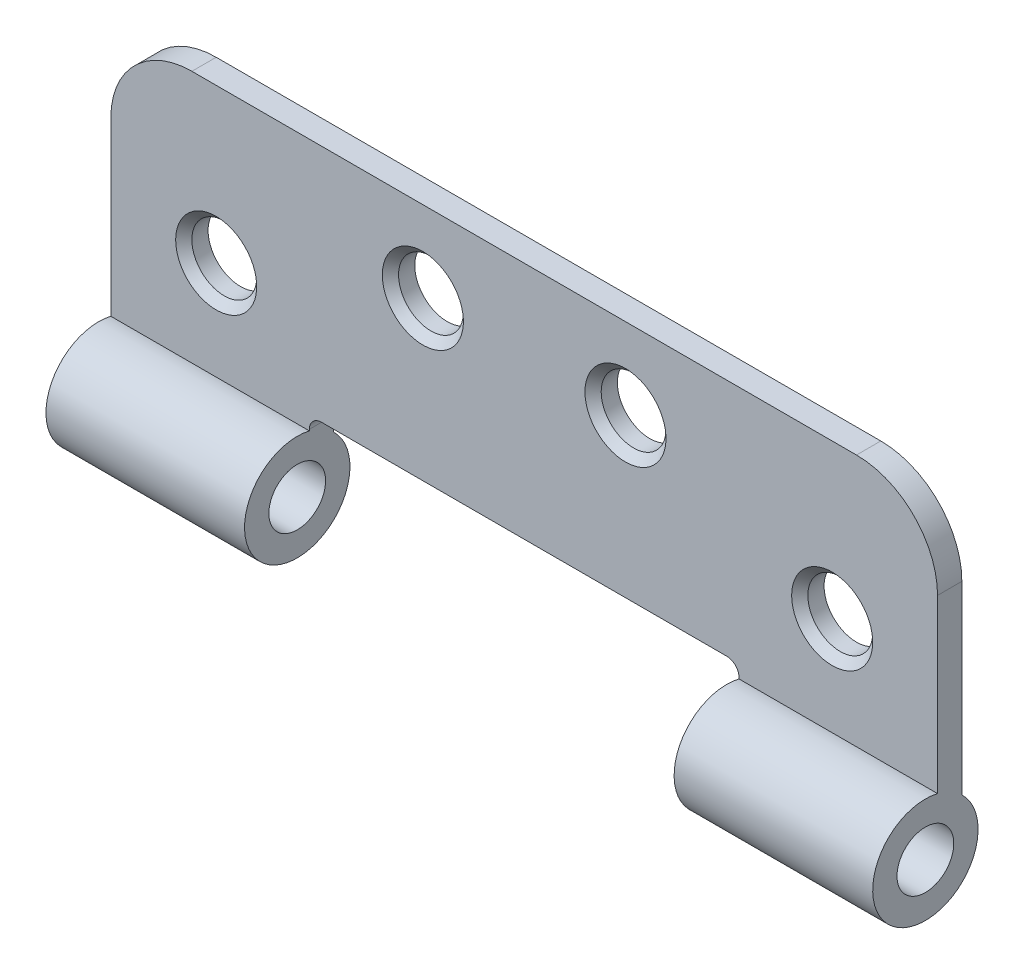
SolidWorks part; units mm, degrees
ref_plane "Front Plane" through (0, 0, 0) normal (0, 0, 1) x (1, 0, 0)
ref_plane "Top Plane" through (0, 0, 0) normal (0, 1, 0) x (1, 0, 0)
ref_plane "Right Plane" through (0, 0, 0) normal (1, 0, 0) x (0, 0, -1)
sketch "Sketch1" plane through (0, 0, 0) normal (0, 0, 1) x (1, 0, 0)
  line L1 (-51, 0) -> (51, 0)
  line L2 (-51, 0) -> (-51, 27.5)
  line L3 (-41, 37.5) -> (41, 37.5)
  line L4 (51, 0) -> (51, 27.5)
  arc A0 (41, 37.5) -> (51, 27.5) centre (41, 27.5) cw
  arc A1 (-51, 27.5) -> (-41, 37.5) centre (-41, 27.5) cw
  circle A2 centre (-38, 18.5) radius 4
  circle A3 centre (38, 18.5) radius 4
  circle A4 centre (-12.5, 27.5) radius 4
  circle A5 centre (12.5, 27.5) radius 4
  point P4 (0, 0)
  point P8 (51, 37.5)
  point P11 (-51, 37.5)
  point P21 (0, 37.5)
  dimension "D3" = 10
  dimension "D4" = 8
  dimension "D5" = 18.5
  dimension "D6" = 27.5
  dimension "D7" = 25
  dimension "D9" = 76
  dimension "D1" = 102
  dimension "D2" = 37.5
  dimension "D8" = 12.5
  dimension "D10" = 38
extrude "Boss-Extrude1" add sketch "Sketch1" along normal blind 3
sketch "Sketch2" plane through (-51, 0, 0) normal (-1, 0, 0) x (0, 0, 1)
  line L0 (0, 27.5) -> (0, 0) construction
  circle A0 centre (4.5, 0) radius 6.5
  dimension "D1" = 13
  dimension "D2" = 4.5
extrude "Boss-Extrude2" add sketch "Sketch2" against normal up to surface (102 mm away) up to face at (51, 13.75, 1.5)
sketch "Sketch3" plane through (-51, 0, 0) normal (-1, 0, 0) x (0, 0, 1)
  circle A0 centre (4.5, 0) radius 3.5
  dimension "D1" = 7
extrude "Cut-Extrude1" cut sketch "Sketch3" against normal through all
sketch "Sketch4" plane through (0, 0, 3) normal (0, 0, 1) x (1, 0, 0)
  line L0 (41, 37.5) -> (-41, 37.5) construction
  line L1 (-26.5, 8) -> (26.5, 8)
  line L2 (-26.5, 8) -> (-26.5, -6.5)
  line L3 (-26.5, -6.5) -> (26.5, -6.5)
  line L4 (26.5, 8) -> (26.5, -6.5)
  line L5 (-51, -6.5) -> (51, -6.5) construction
  point P7 (0, -6.5)
  dimension "D1" = 29.5
  dimension "D2" = 53
extrude "Cut-Extrude2" cut sketch "Sketch4" against normal through all both and the other way through all
fillet "Fillet1" radius 1.5 2 edges at (26.5, 8, 1.5) (-26.5, 8, 1.5)
chamfer "Chamfer1" distance 1 angle 45 4 edges at (42, 18.5, 3) (16.5, 27.5, 3) (-8.5, 27.5, 3) (-34, 18.5, 3)
